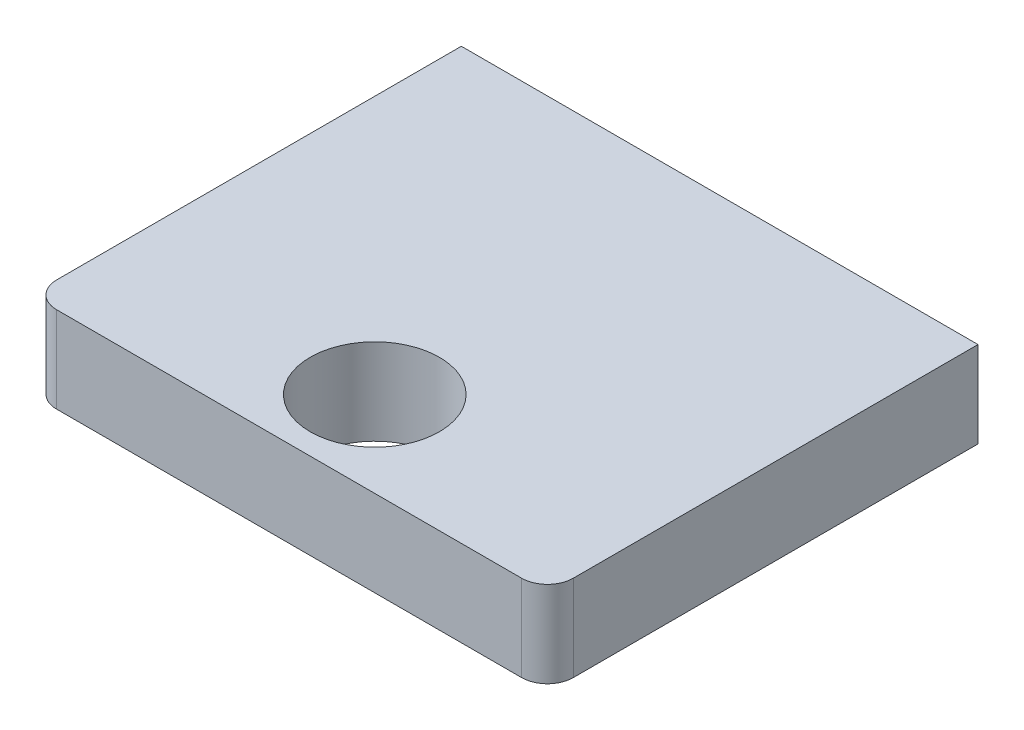
SolidWorks part; units mm, degrees
ref_plane "前视基准面" through (0, 0, 0) normal (0, 0, 1) x (1, 0, 0)
ref_plane "上视基准面" through (0, 0, 0) normal (0, 1, 0) x (1, 0, 0)
ref_plane "右视基准面" through (0, 0, 0) normal (1, 0, 0) x (0, 0, -1)
sketch "草图1" plane through (0, 0, 0) normal (0, 1, 0) x (1, 0, 0)
  line L1 (-30, 25) -> (30, 25)
  line L2 (-30, 25) -> (-30, -25)
  line L3 (-30, -25) -> (30, -25)
  line L4 (30, 25) -> (30, -25)
  line L5 (-30, 25) -> (30, -25) construction
  line L6 (-30, -25) -> (30, 25) construction
  point P0 (0, 0)
  dimension "D1" = 60
  dimension "D2" = 50
extrude "凸台-拉伸1" add sketch "草图1" along normal blind 10
sketch "草图2" plane through (0, 0, 0) normal (0, -1, 0) x (1, 0, 0)
  line L0 (-30, 25) -> (30, 25) construction
  line L2 (0, 25) -> (0, -25) construction
  line L3 (30, -25) -> (-30, -25) construction
  circle A0 centre (-18, 16.9) radius 4
  circle A1 centre (18, 16.9) radius 4
  dimension "D1" = 8
  dimension "D2" = 8.1
  dimension "D4" = 36
extrude "切除-拉伸1" cut sketch "草图2" against normal blind 0.5 contours A1 | A0
fillet "圆角1" radius 3 2 edges at (30, 5, 25) (-30, 5, 25)
sketch "草图3" plane through (0, 10, 0) normal (0, 1, 0) x (1, 0, 0)
  circle A0 centre (0, -15.0529) radius 7.5
  dimension "D1" = 15
extrude "切除-拉伸2" cut sketch "草图3" against normal through all
